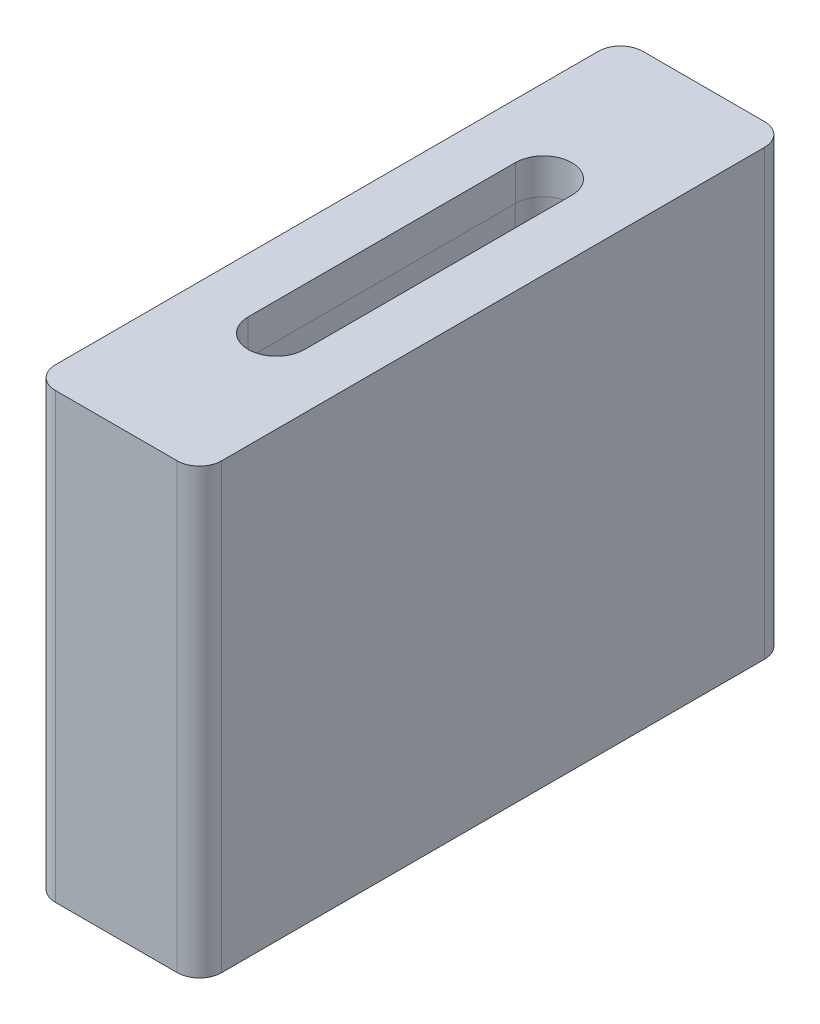
SolidWorks part; units mm, degrees
material "K110"
ref_plane "Front Plane" through (0, 0, 0) normal (0, 0, 1) x (1, 0, 0)
ref_plane "Top Plane" through (0, 0, 0) normal (0, 1, 0) x (1, 0, 0)
ref_plane "Right Plane" through (0, 0, 0) normal (1, 0, 0) x (0, 0, -1)
sketch "Sketch1" plane through (0, 0, 0) normal (0, 1, 0) x (1, 0, 0)
  line L3 (0, -3.5) -> (0, 3.5) construction
  line L4 (-2.62, -3.5) -> (-2.62, 3.5) construction
  line L5 (2.62, -3.5) -> (2.62, 3.5) construction
  line L6 (-5.5, -26.5) -> (5.5, -26.5)
  line L7 (-7.5, -24.5) -> (-7.5, 24.5)
  line L8 (-5.5, 26.5) -> (5.5, 26.5)
  line L9 (7.5, -24.5) -> (7.5, 24.5)
  line L10 (-7.5, -26.5) -> (7.5, 26.5) construction
  line L11 (-7.5, 26.5) -> (7.5, -26.5) construction
  arc A2 (-2.62, -3.5) -> (2.62, -3.5) centre (0, -3.5) ccw construction
  arc A3 (2.62, 3.5) -> (-2.62, 3.5) centre (0, 3.5) ccw construction
  arc A4 (-5.5, -26.5) -> (-7.5, -24.5) centre (-5.5, -24.5) cw
  arc A5 (5.5, -26.5) -> (7.5, -24.5) centre (5.5, -24.5) ccw
  arc A6 (5.5, 26.5) -> (7.5, 24.5) centre (5.5, 24.5) cw
  arc A7 (-7.5, 24.5) -> (-5.5, 26.5) centre (-5.5, 24.5) cw
  point P0 (0, 0)
  point P10 (0, 0)
  dimension "D1" = 7
  dimension "D3" = 2.62
  dimension "D5" = 2
  dimension "D2" = 53
  dimension "D4" = 15
extrude "Boss-Extrude1" add sketch "Sketch1" against normal blind 40
sketch "Sketch5" plane through (0, 0, 0) normal (0, 1, 0) x (1, 0, 0)
  line L0 (0, -12.05) -> (0, 12.05) construction
  line L1 (-2.55, -12.05) -> (-2.55, 12.05)
  line L2 (2.55, -12.05) -> (2.55, 12.05)
  arc A0 (-2.55, -12.05) -> (2.55, -12.05) centre (0, -12.05) ccw
  arc A1 (2.55, 12.05) -> (-2.55, 12.05) centre (0, 12.05) ccw
  point P4 (0, 0)
  dimension "D1" = 24.1
  dimension "D2" = 5.1
extrude "Cut-Extrude2" cut sketch "Sketch5" against normal up to next
sketch "Sketch7" plane through (0, 0, 0) normal (0, 0, 1) x (1, 0, 0)
  line L0 (2.55, -3.2) -> (3.1923, -40)
  line L1 (2.55, -40) -> (2.55, 0) construction
  line L2 (-5.5, -40) -> (5.5, -40) construction
  line L3 (3.1923, -40) -> (2.55, -40)
  line L4 (2.55, -40) -> (2.55, -3.2)
  line L5 (7.5, 0) -> (5.5, 0) construction
  dimension "D1" = 3.2
  dimension "D2" = 1
sketch "Sketch8" plane through (0, 0, 0) normal (0, 1, 0) x (1, 0, 0)
  line L0 (-2.55, 12.05) -> (-2.55, -12.05) construction
  line L1 (2.55, -12.05) -> (2.55, 12.05) construction
  line L2 (-2.55, 12.05) -> (-2.55, -12.05)
  line L3 (2.55, -12.05) -> (2.55, 12.05)
  arc A0 (2.55, 12.05) -> (-2.55, 12.05) centre (0, 12.05) ccw construction
  arc A1 (-2.55, -12.05) -> (2.55, -12.05) centre (0, -12.05) ccw construction
  arc A2 (2.55, 12.05) -> (-2.55, 12.05) centre (0, 12.05) ccw
  arc A3 (-2.55, -12.05) -> (2.55, -12.05) centre (0, -12.05) ccw
sweep "Cut-Sweep1" cut profiles "Sketch7" path "Sketch8"
hole_wizard "M6 Tapped Hole1" positions "Sketch11" profile "Sketch10" tap size "M6" standard "ISO"
sketch "Sketch11" plane through (0, -40, 0) normal (0, -1, 0) x (-1, 0, 0)
  line L0 (-5.5, 26.5) -> (5.5, 26.5) construction
  line L5 (5.5, -26.5) -> (-5.5, -26.5) construction
  line L6 (0, 26.5) -> (0, -26.5) construction
  point P0 (0, 22.5)
  point P2 (0, -22.5)
  dimension "D1" = 4
  dimension "D4" = 4
sketch "Sketch10" plane through (0, -40, -22.5) normal (1, 0, 0) x (0, 0, -1)
  line L0 (0, 0) -> (0, 18.5022)
  line L1 (0, 18.5022) -> (2.5, 17)
  line L2 (2.5, 17) -> (2.5, 0.525)
  line L3 (2.5, 0.525) -> (3.025, 0)
  line L5 (3.025, 0) -> (0, 0)
  line L6 (-2.5, 0.525) -> (-3.025, 0) construction
  line L10 (0, 18.5022) -> (-2.5, 17) construction
  line L11 (0, -6.35) -> (0, 107.95) construction
  dimension "Tap Drill Dia." = 5
  dimension "Tap Drill Depth" = 17
  dimension "Near C'Sink Dia." = 6.05
  dimension "Near C'Sink Angle" = 90
  dimension "Drill Angle" = 118
cosmetic thread "Hole Thread1"
cosmetic thread "Hole Thread2"
